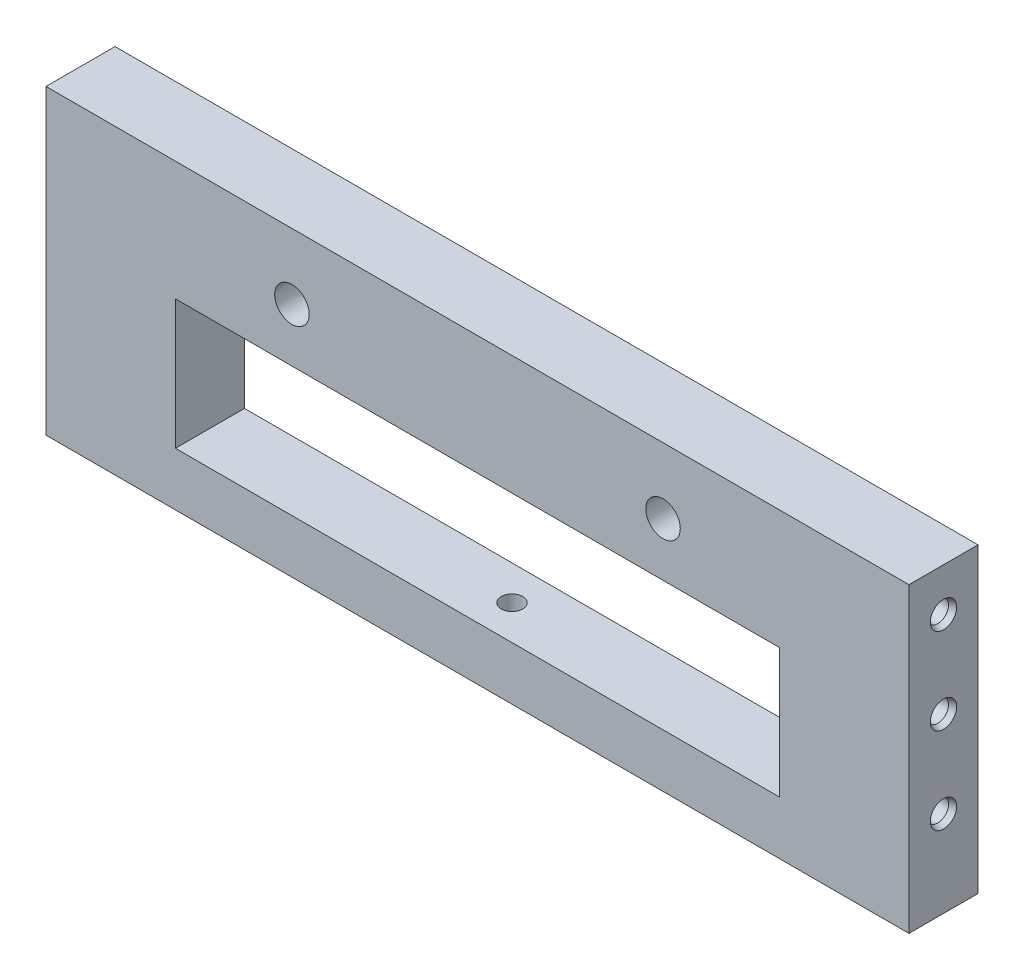
SolidWorks part; units mm, degrees
ref_plane "前基準面" through (0, 0, 0) normal (0, 0, 1) x (1, 0, 0)
ref_plane "上基準面" through (0, 0, 0) normal (0, 1, 0) x (1, 0, 0)
ref_plane "右基準面" through (0, 0, 0) normal (1, 0, 0) x (0, 0, -1)
sketch "草圖1" plane through (0, 0, 0) normal (0, 0, 1) x (1, 0, 0)
  line L0 (0, 0) -> (-50, 0)
  line L1 (-50, 0) -> (-50, 35)
  line L2 (-50, 35) -> (50, 35)
  line L3 (50, 35) -> (50, 0)
  line L4 (50, 0) -> (0, 0)
  line L5 (0, 0) -> (0, 27.37)
  line L6 (0, 27.37) -> (-21.5, 27.37) construction
  line L7 (0, 27.37) -> (21.5, 27.37) construction
  line L9 (-35, 6.185) -> (35, 6.185)
  line L10 (-35, 6.185) -> (-35, 21.185)
  line L11 (-35, 21.185) -> (35, 21.185)
  line L12 (35, 6.185) -> (35, 21.185)
  line L13 (-35, 6.185) -> (35, 21.185) construction
  line L14 (-35, 21.185) -> (35, 6.185) construction
  circle A0 centre (-21.5, 27.37) radius 2
  circle A1 centre (21.5, 27.37) radius 2
  point P12 (0, 13.685)
  dimension "D5" = 4
  dimension "D1" = 27.37
  dimension "D2" = 35
  dimension "D3" = 50
  dimension "D4" = 21.5
  dimension "D6" = 70
  dimension "D7" = 15
extrude "填料-伸長2" add sketch "草圖1" along normal blind 8
ref_plane "平面1" through (0, 0, 0) normal (0, -1, 0) x (-1, 0, 0)
sketch "草圖2" plane through (0, 0, 0) normal (0, -1, 0) x (-1, 0, 0)
  line L0 (0, 0) -> (0, -4)
  line L1 (0, -4) -> (-20, -4) construction
  line L2 (-20, -4) -> (-40, -4) construction
  line L3 (0, -4) -> (20, -4) construction
  line L4 (20, -4) -> (40, -4) construction
  circle A0 centre (-40, -4) radius 1.3
  circle A2 centre (0, -4) radius 1.3
  circle A4 centre (40, -4) radius 1.3
  dimension "D3" = 2.6
  dimension "D1" = 4
  dimension "D2" = 20
ref_plane "平面2" through (50, 0, 0) normal (1, 0, 0) x (0, 0, -1)
sketch "草圖3" plane through (50, 0, 0) normal (1, 0, 0) x (0, 0, -1)
  line L0 (0, 0) -> (-4, 0) construction
  line L1 (-8, 0) -> (0, 0) construction
  line L2 (-4, 0) -> (-4, 10) construction
  line L3 (-4, 10) -> (-4, 20) construction
  line L4 (-4, 20) -> (-4, 30) construction
  circle A1 centre (-4, 20) radius 1.3
  circle A2 centre (-4, 10) radius 1.3
  circle A3 centre (-4, 30) radius 1.3
  dimension "D1" = 10
  dimension "D2" = 2.6
ref_plane "平面3" through (-50, 0, 0) normal (-1, 0, 0) x (0, 0, 1)
sketch "草圖4" plane through (-50, 0, 0) normal (-1, 0, 0) x (0, 0, 1)
  line L0 (0, 0) -> (4, 0) construction
  line L1 (-4.4, 0) -> (4.4, 0) construction
  line L2 (4, 0) -> (4, 10) construction
  line L3 (4, 10) -> (4, 20) construction
  line L4 (4, 20) -> (4, 30) construction
  circle A1 centre (4, 20) radius 1.3
  circle A2 centre (4, 10) radius 1.3
  circle A3 centre (4, 30) radius 1.3
  dimension "D2" = 2.6
  dimension "D1" = 4
  dimension "D3" = 10
hole_wizard "M3 螺紋孔1" positions "3D草圖1" profile "草圖5" tap size "M3" standard "ISO"
sketch3d "3D草圖1"
  point P0 (50, 30, 4)
  point P3 (50, 30, 4)
  point P4 (50, 20, 4)
  point P5 (50, 10, 4)
sketch "草圖5" plane through (50, 10, 4) normal (0, 1, 0) x (0, 0, -1)
  line L0 (0, 0) -> (0, 7.5)
  line L1 (0, 7.5) -> (1.25, 6.7489)
  line L2 (1.25, 6.7489) -> (1.25, 0.6639)
  line L3 (1.25, 0.6639) -> (1.525, 0)
  line L5 (1.525, 0) -> (0, 0)
  line L6 (-1.25, 0.6639) -> (-1.525, 0) construction
  line L10 (0, 7.5) -> (-1.25, 6.7489) construction
  line L11 (0, -6.35) -> (0, 107.95) construction
  dimension "螺孔鑽直徑" = 2.5
  dimension "螺孔鑽深度" = 7.5
  dimension "近端錐孔直徑" = 3.05
  dimension "近端錐孔角度" = 45
  dimension "導頭角度" = 118
hole_wizard "M3 螺紋孔2" positions "3D草圖2" profile "草圖6" tap size "M3" standard "ISO"
sketch3d "3D草圖2"
  point P0 (-50, 30, 4)
  point P2 (-50, 20, 4)
  point P4 (-50, 10, 4)
sketch "草圖6" plane through (-50, 30, 4) normal (0, 1, 0) x (0, 0, 1)
  line L0 (0, 0) -> (0, 7.5)
  line L1 (0, 7.5) -> (1.25, 6.7489)
  line L2 (1.25, 6.7489) -> (1.25, 0.6639)
  line L3 (1.25, 0.6639) -> (1.525, 0)
  line L5 (1.525, 0) -> (0, 0)
  line L6 (-1.25, 0.6639) -> (-1.525, 0) construction
  line L10 (0, 7.5) -> (-1.25, 6.7489) construction
  line L11 (0, -6.35) -> (0, 107.95) construction
  dimension "螺孔鑽直徑" = 2.5
  dimension "螺孔鑽深度" = 7.5
  dimension "近端錐孔直徑" = 3.05
  dimension "近端錐孔角度" = 45
  dimension "導頭角度" = 118
hole_wizard "M3 螺紋孔3" positions "3D草圖4" profile "草圖7" tap size "M3" standard "ISO"
sketch3d "3D草圖4"
  point P0 (40, 0, 4)
  point P2 (0, 0, 4)
  point P4 (-40, 0, 4)
sketch "草圖7" plane through (40, 0, 4) normal (1, 0, 0) x (0, 0, -1)
  line L0 (0, 0) -> (0, 7.5)
  line L1 (0, 7.5) -> (1.25, 6.7489)
  line L2 (1.25, 6.7489) -> (1.25, 0.6639)
  line L3 (1.25, 0.6639) -> (1.525, 0)
  line L5 (1.525, 0) -> (0, 0)
  line L6 (-1.25, 0.6639) -> (-1.525, 0) construction
  line L10 (0, 7.5) -> (-1.25, 6.7489) construction
  line L11 (0, -6.35) -> (0, 107.95) construction
  dimension "螺孔鑽直徑" = 2.5
  dimension "螺孔鑽深度" = 7.5
  dimension "近端錐孔直徑" = 3.05
  dimension "近端錐孔角度" = 45
  dimension "導頭角度" = 118
